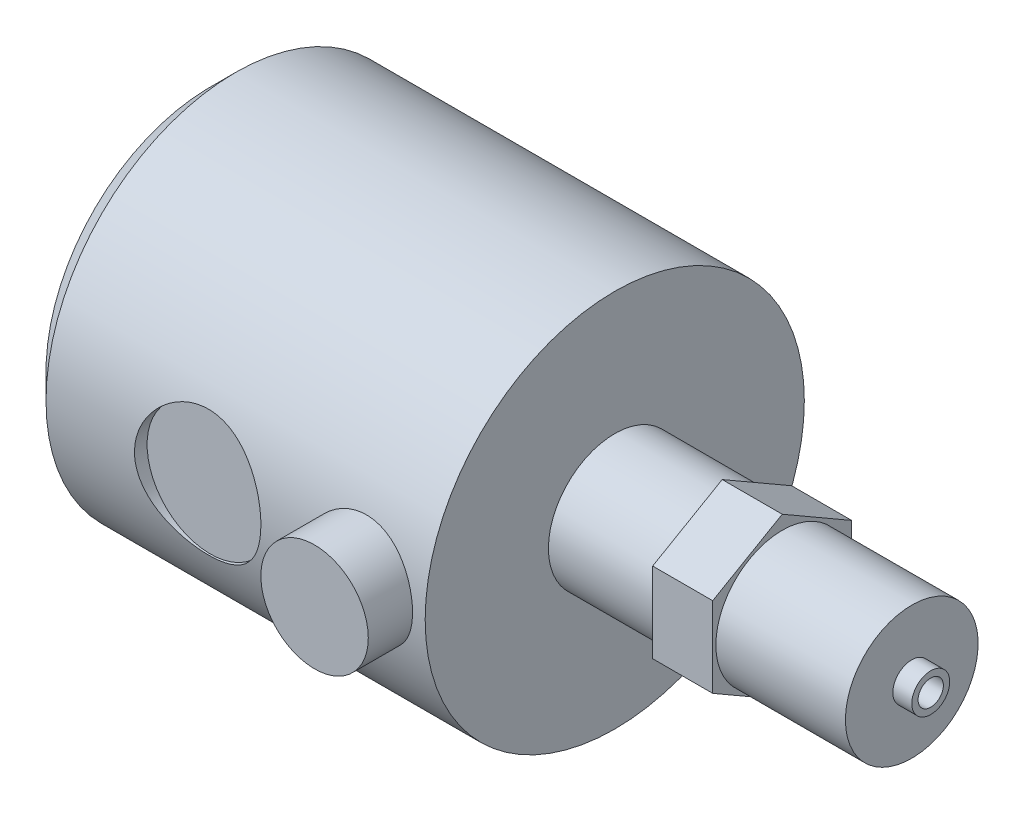
SolidWorks part; units mm, degrees
ref_plane "Front Plane" through (0, 0, 0) normal (0, 0, 1) x (1, 0, 0)
ref_plane "Top Plane" through (0, 0, 0) normal (0, 1, 0) x (1, 0, 0)
ref_plane "Right Plane" through (0, 0, 0) normal (1, 0, 0) x (0, 0, -1)
sketch "Skica1" plane through (0, 0, 0) normal (0, 0, 1) x (1, 0, 0)
  line L0 (0, 0) -> (114.1803, 0) construction
  line L1 (0, 0) -> (0, 30)
  line L2 (0, 30) -> (64, 30)
  line L3 (64, 30) -> (64, 10.5)
  line L4 (64, 10.5) -> (111, 10.5)
  line L5 (111, 10.5) -> (111, 0)
  line L6 (111, 0) -> (0, 0)
  dimension "D1" = 64
  dimension "D2" = 60
  dimension "D3" = 21
  dimension "D4" = 111
revolve "Rotovat1" add sketch "Skica1" angle 360 about L0
chamfer "Zkosení1" distance 4 angle 45 1 edges at (0, 0, 30)
ref_plane "Rovina1" through (0, 0, 30) normal (0, 0, 1) x (1, 0, 0)
sketch "Skica2" plane through (0, 0, 30) normal (0, 0, 1) x (1, 0, 0)
  line L0 (64, -30) -> (64, 30) construction
  circle A0 centre (28, 0) radius 10
  dimension "D1" = 20
  dimension "D2" = 36
extrude "Odebrat vysunutím1" cut sketch "Skica2" against normal blind 2
ref_plane "Rovina2" through (81, 0, 0) normal (1, 0, 0) x (0, 0, -1)
sketch "Skica3" plane through (81, 0, 0) normal (1, 0, 0) x (0, 0, -1)
  line L1 (0, 12.7017) -> (-11, 6.3509)
  line L2 (-11, 6.3509) -> (-11, -6.3509)
  line L3 (-11, -6.3509) -> (0, -12.7017)
  line L4 (0, -12.7017) -> (11, -6.3509)
  line L5 (11, -6.3509) -> (11, 6.3509)
  line L6 (11, 6.3509) -> (0, 12.7017)
  circle A0 centre (0, 0) radius 11 construction
  dimension "D1" = 22
extrude "Přidat vysunutím1" add sketch "Skica3" along normal blind 9.5
sketch "Skica4" plane through (111, 0, 0) normal (1, 0, 0) x (0, 0, -1)
  circle A0 centre (0, 0) radius 2
  circle A1 centre (0, 0) radius 3
  dimension "D1" = 4
  dimension "D2" = 6
extrude "Přidat vysunutím2" add sketch "Skica4" along normal blind 3
sketch "Skica5" plane through (0, 0, 28) normal (0, 0, 1) x (1, 0, 0)
  line L0 (64, -30) -> (64, 30) construction
  circle A0 centre (53.5, 0) radius 8.5
  point P2 (0, 0)
  point P4 (52.5403, 0)
  dimension "D1" = 17
  dimension "D2" = 2
extrude "Přidat vysunutím3" add sketch "Skica5" along normal blind 9
